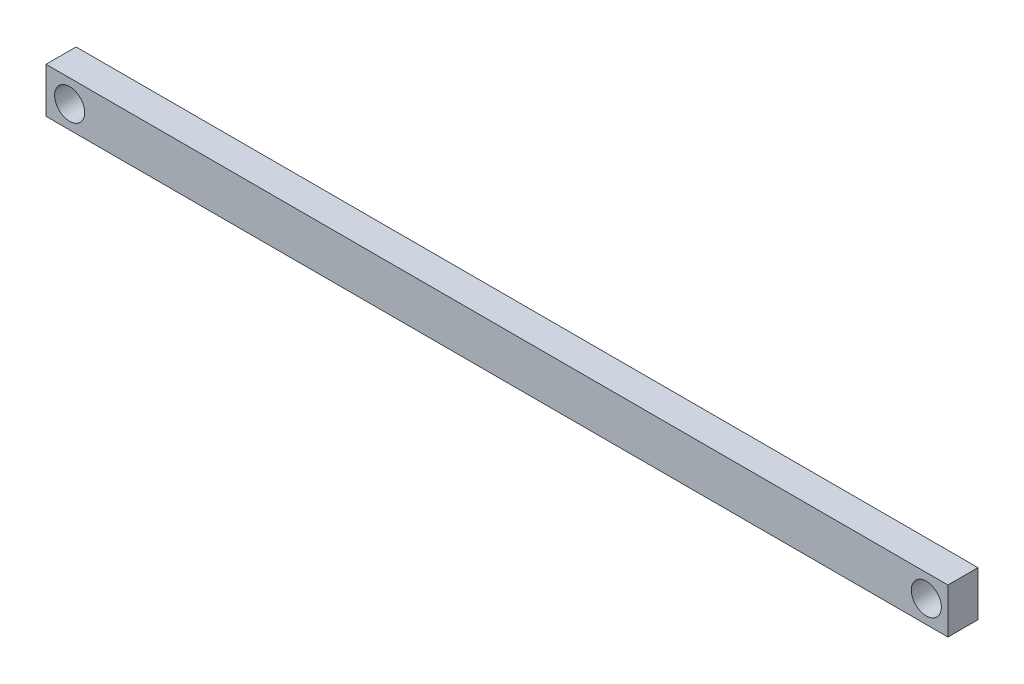
SolidWorks part; units mm, degrees
ref_plane "前视基准面" through (0, 0, 0) normal (0, 0, 1) x (1, 0, 0)
ref_plane "上视基准面" through (0, 0, 0) normal (0, 1, 0) x (1, 0, 0)
ref_plane "右视基准面" through (0, 0, 0) normal (1, 0, 0) x (0, 0, -1)
sketch "草图1" plane through (0, 0, 0) normal (0, 0, 1) x (1, 0, 0)
  line L1 (-58.1347, 21.3721) -> (241.8653, 21.3721)
  line L2 (-58.1347, 21.3721) -> (-58.1347, 6.3721)
  line L3 (-58.1347, 6.3721) -> (241.8653, 6.3721)
  line L4 (241.8653, 21.3721) -> (241.8653, 6.3721)
  circle A0 centre (-50.2787, 13.8721) radius 5
  circle A1 centre (234.6762, 13.8721) radius 5
  point P6 (184.8801, 13.8721)
  point P9 (230.4975, 13.8721)
  point P10 (234.6762, 13.8721)
extrude "凸台-拉伸1" add sketch "草图1" along normal blind 10
